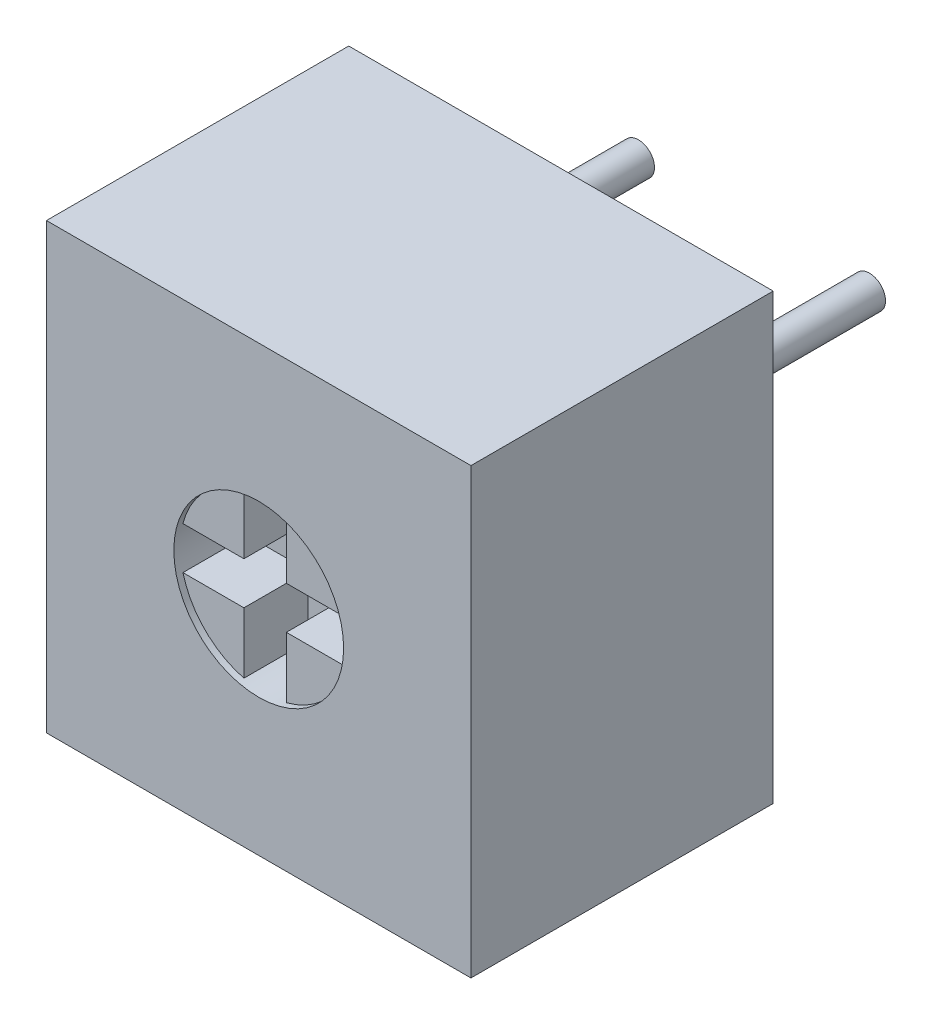
SolidWorks part; units mm, degrees
other "Детальный элемент1"
ref_plane "Спереди" through (0, 0, 0) normal (0, 0, 1) x (1, 0, 0)
ref_plane "Сверху" through (0, 0, 0) normal (0, 1, 0) x (1, 0, 0)
ref_plane "Справа" through (0, 0, 0) normal (1, 0, 0) x (0, 0, -1)
sketch "Эскиз1" plane through (0, 0, 0) normal (0, 0, 1) x (1, 0, 0)
  line L1 (-3.3, -3.45) -> (3.3, -3.45)
  line L2 (-3.3, -3.45) -> (-3.3, 3.45)
  line L3 (-3.3, 3.45) -> (3.3, 3.45)
  line L4 (3.3, -3.45) -> (3.3, 3.45)
  line L5 (-3.3, -3.45) -> (3.3, 3.45) construction
  line L6 (-3.3, 3.45) -> (3.3, -3.45) construction
  point P0 (0, 0)
  dimension "D1" = 6.6
  dimension "D2" = 6.9
extrude "Бобышка-Вытянуть1" add sketch "Эскиз1" along normal blind 4.7
sketch "Эскиз2" plane through (0, 0, 4.7) normal (0, 0, 1) x (1, 0, 0)
  circle A0 centre (0, 0) radius 1.32
  dimension "D1" = 2.64
extrude "Вырез-Вытянуть1" cut sketch "Эскиз2" against normal blind 0.1
sketch "Эскиз3" plane through (0, 0, 4.6) normal (0, 0, 1) x (1, 0, 0)
  line L0 (-0.33, 1.2781) -> (-0.33, 0.33)
  line L1 (-0.33, 0.33) -> (-1.2781, 0.33)
  line L3 (-1.2781, -0.33) -> (-0.33, -0.33)
  line L4 (-0.33, -0.33) -> (-0.33, -1.2781)
  line L6 (0.33, -1.2781) -> (0.33, -0.33)
  line L7 (0.33, -0.33) -> (1.2781, -0.33)
  line L9 (1.2781, 0.33) -> (0.33, 0.33)
  line L10 (0.33, 0.33) -> (0.33, 1.2781)
  circle A0 centre (0, 0) radius 1.32 construction
  arc A1 (-1.2781, -0.33) -> (-1.2781, 0.33) centre (0, 0) cw
  arc A2 (-0.33, 1.2781) -> (0.33, 1.2781) centre (0, 0) cw
  arc A3 (1.2781, 0.33) -> (1.2781, -0.33) centre (0, 0) cw
  arc A4 (0.33, -1.2781) -> (-0.33, -1.2781) centre (0, 0) cw
  point P15 (0, 0)
  dimension "D1" = 0.66
extrude "Вырез-Вытянуть2" cut sketch "Эскиз3" against normal blind 1
sketch "Эскиз4" plane through (0, 0, 0) normal (0, 0, 1) x (1, 0, 0)
  line L0 (3.3, 3.45) -> (-3.3, 3.45) construction
  circle A0 centre (1.796, 1.19) radius 0.25
  circle A1 centre (-1.7961, 1.19) radius 0.25
  circle A2 centre (0, -0.61) radius 0.25
  point P6 (0, 0)
  point P8 (0, 0)
  point P9 (-2.2078, 2.1031)
  dimension "D5" = 0.5
  dimension "D1" = 1.8
  dimension "D2" = 4.06
  dimension "D3" = 1.796
  dimension "D4" = 1.796
extrude "Бобышка-Вытянуть2" add sketch "Эскиз4" against normal blind 3
